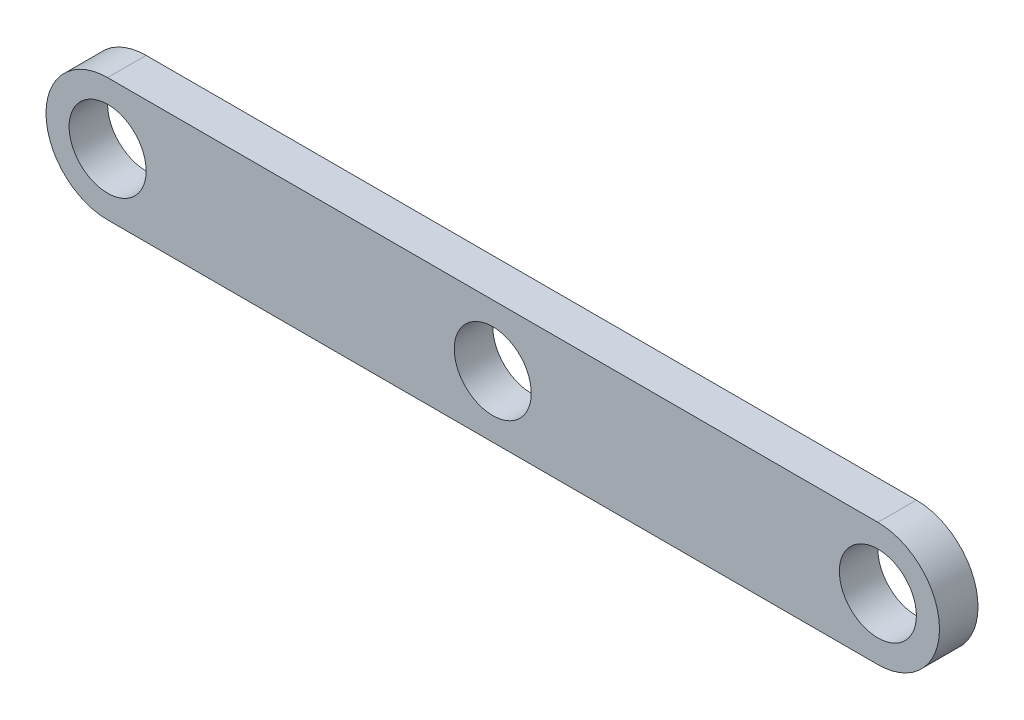
SolidWorks part; units mm, degrees
material "Acrylic (Medium-high impact)"
ref_plane "Front Plane" through (0, 0, 0) normal (0, 0, 1) x (1, 0, 0)
ref_plane "Top Plane" through (0, 0, 0) normal (0, 1, 0) x (1, 0, 0)
ref_plane "Right Plane" through (0, 0, 0) normal (1, 0, 0) x (0, 0, -1)
sketch "Sketch1" plane through (0, 0, 0) normal (0, 0, 1) x (1, 0, 0)
  line L0 (-50, 0) -> (50, 0) construction
  line L1 (-50, 8) -> (50, 8)
  line L2 (-50, -8) -> (50, -8)
  arc A0 (-50, 8) -> (-50, -8) centre (-50, 0) ccw
  arc A1 (50, -8) -> (50, 8) centre (50, 0) ccw
  circle A2 centre (-50, 0) radius 5
  circle A3 centre (50, 0) radius 5
  circle A4 centre (0, 0) radius 5
  point P2 (0, 0)
  dimension "D3" = 10
  dimension "D1" = 100
  dimension "D2" = 16
extrude "Boss-Extrude1" add sketch "Sketch1" along normal mid plane 5
